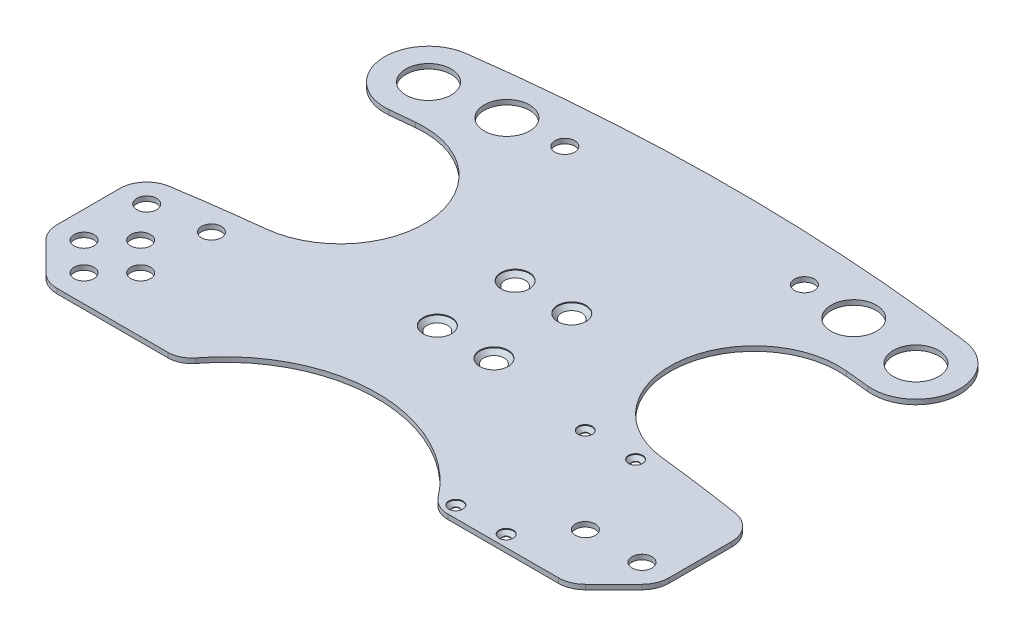
SolidWorks part; units mm, degrees
ref_plane "Front Plane" through (0, 0, 0) normal (0, 0, 1) x (1, 0, 0)
ref_plane "Top Plane" through (0, 0, 0) normal (0, 1, 0) x (1, 0, 0)
ref_plane "Right Plane" through (0, 0, 0) normal (1, 0, 0) x (0, 0, -1)
sketch "Sketch1" plane through (0, 0, 0) normal (0, 1, 0) x (1, 0, 0)
  line L1 (-120, -95) -> (120, -95)
  line L2 (-120, -95) -> (-120, 95)
  line L3 (-120, 95) -> (120, 95)
  line L4 (120, -95) -> (120, 95)
  line L5 (-120, -95) -> (120, 95) construction
  line L6 (-120, 95) -> (120, -95) construction
  line L7 (-10, 13.75) -> (10, 13.75)
  line L8 (-10, 13.75) -> (-10, -13.75)
  line L9 (-10, -13.75) -> (10, -13.75)
  line L10 (10, 13.75) -> (10, -13.75)
  line L11 (-10, 13.75) -> (10, -13.75) construction
  line L12 (-10, -13.75) -> (10, 13.75) construction
  circle A0 centre (0, 0) radius 95
  circle A1 centre (-10, 13.75) radius 2.5
  circle A2 centre (10, 13.75) radius 2.5
  circle A3 centre (10, -13.75) radius 2.5
  circle A4 centre (-10, -13.75) radius 2.5
  circle A5 centre (0, 0) radius 120
  dimension "D3" = 5
  dimension "D1" = 240
  dimension "D2" = 190
  dimension "D4" = 27.5
  dimension "D5" = 20
extrude "Boss-Extrude1" add sketch "Sketch1" along normal blind 1.7 contours A0 A4 L8 A1 L7 A2 L10 A3 L9 | A4 L9 A3 L10 A2 L7 A1 L8 | L3 A5 L1 A0 | L1 A5 L3 A0
sketch "Sketch2" plane through (0, 1.7, 0) normal (0, 1, 0) x (1, 0, 0)
  line L0 (-81.1673, -40) -> (21.9115, -40) construction
  line L1 (-127.3056, -60) -> (138.909, -60) construction
  line L2 (-88.5406, 28.139) -> (-88.5406, -89.0376) construction
  line L3 (-88.5406, -40) -> (-88.5406, -60) construction
  line L4 (0, 21.6044) -> (0, -21.4213) construction
  line L5 (88.5406, 33.139) -> (88.5406, -84.0376) construction
  line L6 (-151.9803, -25) -> (55.006, -25) construction
  line L7 (-48.8837, 35) -> (62.426, 35) construction
  circle A0 centre (0, 0) radius 35
  circle A1 centre (0, 35) radius 2.5
  circle A2 centre (30.3109, 17.5) radius 2.5
  circle A3 centre (30.3109, -17.5) radius 2.5
  circle A4 centre (0, -35) radius 2.5
  circle A5 centre (-30.3109, -17.5) radius 2.5
  circle A6 centre (-30.3109, 17.5) radius 2.5
  circle A7 centre (-88.5406, -40) radius 3.5
  circle A8 centre (-88.5406, -50) radius 10
  circle A9 centre (-78.5406, -50) radius 3.5
  circle A10 centre (-88.5406, -60) radius 3.5
  circle A11 centre (-98.5406, -50) radius 3.5
  circle A12 centre (78.5406, -50) radius 3.5
  circle A13 centre (98.5406, -50) radius 3.5
  circle A14 centre (-98.5406, -27.8625) radius 3.5
  circle A15 centre (-78.5406, -25) radius 3.5
  circle A16 centre (0, 0) radius 45
  circle A17 centre (0, -580) radius 625
  circle A18 centre (0, -580) radius 645
  circle A19 centre (-86.0945, 59.2282) radius 8
  circle A20 centre (-61.2596, 62.0843) radius 8
  circle A21 centre (-86.0945, 59.2282) radius 15.5
  arc A22 (-73.3144, 95) -> (-73.3144, -95) centre (0, 0) ccw construction
  circle A23 centre (-61.2596, 62.0843) radius 9.5
  circle A24 centre (-86.0945, 59.2282) radius 9.5
  circle A25 centre (61.2596, 62.0843) radius 8
  circle A26 centre (86.0945, 59.2282) radius 8
  circle A27 centre (-42.3209, 63.6101) radius 3.5
  circle A28 centre (0, 0) radius 70
  circle A29 centre (42.3209, 63.6101) radius 3.5
  circle A30 centre (-98.5406, -50) radius 9.5
  circle A31 centre (42.3209, 63.6101) radius 9.5
  circle A32 centre (61.2596, 62.0843) radius 9.5
  circle A33 centre (0, -645.0455) radius 625
  point P17 (0, 0)
  point P21 (-88.5406, -50)
  point P37 (-88.5406, -50)
  point P56 (0, 65)
  point P57 (0, 45)
  point P68 (-76.6704, 60.4269)
  point P69 (-70.7097, 61.1124)
  point P81 (0, 0)
  dimension "D1" = 70
  dimension "D2" = 5
  dimension "D4" = 7
  dimension "D9" = 90
  dimension "D10" = 1250
  dimension "D11" = 20
  dimension "D12" = 16
  dimension "D14" = 6
  dimension "D13" = 19
  dimension "D17" = 140
  dimension "D18" = 6
  dimension "D5" = 20
  dimension "D6" = 40
  dimension "D8" = 15
  dimension "D15" = 6
  dimension "D3" = 6
  dimension "D7" = 4
extrude "Cut-Extrude1" cut sketch "Sketch2" against normal up to next contours A7 | A9 | A10 | A11 | A12 | A13 | A14 | A15 | A19 | A20 | A25 | A26 | A27 | A29
sketch "Sketch3" plane through (0, 1.7, 0) normal (0, 1, 0) x (1, 0, 0)
  line L1 (-84.5506, 43.8053) -> (-40.7771, 48.1872)
  line L2 (0, 100.6986) -> (0, -98.8678) construction
  line L3 (-10.3445, 0) -> (20.4144, 0) construction
  line L5 (84.5506, 43.8053) -> (40.7771, 48.1872)
  line L6 (-42.3209, 63.6101) -> (0, 0) construction
  line L7 (-36.306, 26.5871) -> (-55.2257, 55.0243)
  line L8 (-10.4964, 43.7587) -> (-29.4161, 72.1959)
  line L9 (10.4964, 43.7587) -> (29.4161, 72.1959)
  line L10 (36.306, 26.5871) -> (55.2257, 55.0243)
  line L11 (-108.0406, -50) -> (-108.0406, -27.8625)
  line L13 (-73.3144, -95) -> (73.3144, -95)
  line L14 (73.3144, 95) -> (-73.3144, 95)
  line L15 (-73.3144, -95) -> (73.3144, -95)
  line L16 (73.3144, 95) -> (-73.3144, 95)
  line L17 (-69.0406, -25) -> (-69.0406, -50)
  line L18 (-71.8231, -56.7175) -> (-81.8231, -66.7175)
  line L19 (-105.2581, -56.7175) -> (-95.2581, -66.7175)
  line L20 (-42.3209, 79.1101) -> (42.3209, 79.1101)
  line L21 (-78.5406, -15.5) -> (-42.2463, -15.5)
  line L22 (0, -45) -> (111.243, -45) construction
  line L23 (-88.5406, -69.5) -> (88.5406, -69.5)
  line L24 (69.0406, -15.5) -> (45.0406, -15.5)
  line L25 (78.5406, -15.5) -> (42.2463, -15.5)
  line L27 (108.0406, -50) -> (108.0406, -27.8625)
  line L28 (105.2581, -56.7175) -> (95.2581, -66.7175)
  line L29 (69.0406, -15.5) -> (69.0406, -69.5)
  line L30 (69.0406, -69.5) -> (45.0406, -69.5)
  line L31 (45.0406, -15.5) -> (45.0406, -69.5)
  line L32 (57.0406, -15.5) -> (57.0406, -69.5) construction
  line L33 (45.0406, -42.5) -> (69.0406, -42.5) construction
  circle A0 centre (-86.0945, 59.2282) radius 15.5
  arc A1 (-73.3144, 95) -> (-73.3144, -95) centre (0, 0) ccw construction
  circle A2 centre (-42.3209, 63.6101) radius 15.5
  circle A3 centre (86.0945, 59.2282) radius 15.5
  circle A4 centre (42.3209, 63.6101) radius 15.5
  circle A5 centre (0, 0) radius 45
  circle A6 centre (-98.5406, -27.8625) radius 9.5
  circle A7 centre (-98.5406, -27.8625) radius 3.5 construction
  arc A8 (-73.3144, 95) -> (-73.3144, -95) centre (0, 0) ccw
  arc A9 (73.3144, -95) -> (73.3144, 95) centre (0, 0) ccw
  arc A10 (-73.3144, 95) -> (-73.3144, -95) centre (0, 0) ccw
  arc A11 (73.3144, -95) -> (73.3144, 95) centre (0, 0) ccw
  circle A12 centre (-78.5406, -25) radius 9.5
  circle A13 centre (-88.5406, -60) radius 9.5
  circle A14 centre (-98.5406, -50) radius 9.5
  circle A15 centre (-78.5406, -50) radius 9.5
  circle A17 centre (98.5406, -50) radius 9.5
  circle A18 centre (78.5406, -50) radius 9.5
  arc A19 (73.3144, -95) -> (73.3144, 95) centre (0, 0) ccw construction
  arc A20 (-45.0406, -69.5) -> (45.0406, -69.5) centre (0, -98.6511) cw
  circle A21 centre (98.5406, -27.8625) radius 9.5
  circle A22 centre (98.5406, -50) radius 9.5
  circle A23 centre (88.5406, -60) radius 9.5
  circle A24 centre (-73.1485, 15.1063) radius 29.692
  circle A25 centre (73.1485, 15.1063) radius 29.692
  circle A26 centre (48.1506, -19.64) radius 1.3
  circle A27 centre (65.9306, -19.64) radius 1.3
  circle A28 centre (65.9306, -65.36) radius 1.3
  circle A29 centre (48.1506, -65.36) radius 1.3
  circle A30 centre (0, -580) radius 645
  circle A31 centre (0, -580) radius 660.5
  circle A32 centre (0, -645.0455) radius 634.5
  dimension "D1" = 90
  dimension "D3" = 6
  dimension "D5" = 2.6
  dimension "D4" = 24
  dimension "D6" = 17.78
  dimension "D7" = 45.72
  dimension "D2" = 0
extrude "Cut-Extrude2" cut sketch "Sketch3" against normal up to next
hole_wizard "CSK for M5 Flat Head Machine Screw1" positions "Sketch4" profile "Sketch5" countersink size "M5" standard "ANSI Metric"
sketch "Sketch4" plane through (0, 1.7, 0) normal (0, 1, 0) x (1, 0, 0)
  point P0 (-10, 13.75)
  point P3 (10, 13.75)
  point P6 (10, -13.75)
  point P9 (-10, -13.75)
sketch "Sketch5" plane through (-10, 1.7, -13.75) normal (1, 0, 0) x (0, 0, 1)
  line L0 (0, 0) -> (0, 6.5022)
  line L1 (0, 6.5022) -> (2.5, 5)
  line L2 (2.5, 5) -> (2.5, 2.8)
  line L3 (2.5, 2.8) -> (5, 0.3)
  line L4 (5, 0.3) -> (5, 0)
  line L6 (5, 0) -> (0, 0)
  line L7 (-2.5, 2.8) -> (-5, 0.3) construction
  line L10 (0, 6.5022) -> (-2.5, 5) construction
  line L11 (0, -6.35) -> (0, 107.95) construction
  dimension "Hole Dia." = 5
  dimension "Hole Depth" = 5
  dimension "C'Sink Dia." = 10
  dimension "C'Sink Angle" = 90
  dimension "Drill Angle" = 118
  dimension "Head Clearance" = 0.3
hole_wizard "CSK for M2.5 Flat Head Machine Screw1" positions "Sketch6" profile "Sketch7" countersink size "M2.5" standard "ANSI Metric"
sketch "Sketch6" plane through (0, 1.7, 0) normal (0, 1, 0) x (1, 0, 0)
  point P0 (48.1506, -19.64)
  point P3 (65.9306, -19.64)
  point P6 (65.9306, -65.36)
  point P9 (48.1506, -65.36)
sketch "Sketch7" plane through (48.1506, 1.7, 19.64) normal (1, 0, 0) x (0, 0, 1)
  line L0 (0, 0) -> (0, 5.7511)
  line L1 (0, 5.7511) -> (1.25, 5)
  line L2 (1.25, 5) -> (1.25, 1.55)
  line L3 (1.25, 1.55) -> (2.5, 0.3)
  line L4 (2.5, 0.3) -> (2.5, 0)
  line L6 (2.5, 0) -> (0, 0)
  line L7 (-1.25, 1.55) -> (-2.5, 0.3) construction
  line L10 (0, 5.7511) -> (-1.25, 5) construction
  line L11 (0, -6.35) -> (0, 107.95) construction
  dimension "Hole Dia." = 2.5
  dimension "Hole Depth" = 5
  dimension "C'Sink Dia." = 5
  dimension "C'Sink Angle" = 90
  dimension "Drill Angle" = 118
  dimension "Head Clearance" = 0.3
fillet "Fillet1" radius 8.5 2 edges at (45.0406, 0.85, 69.5) (-45.0406, 0.85, 69.5)
